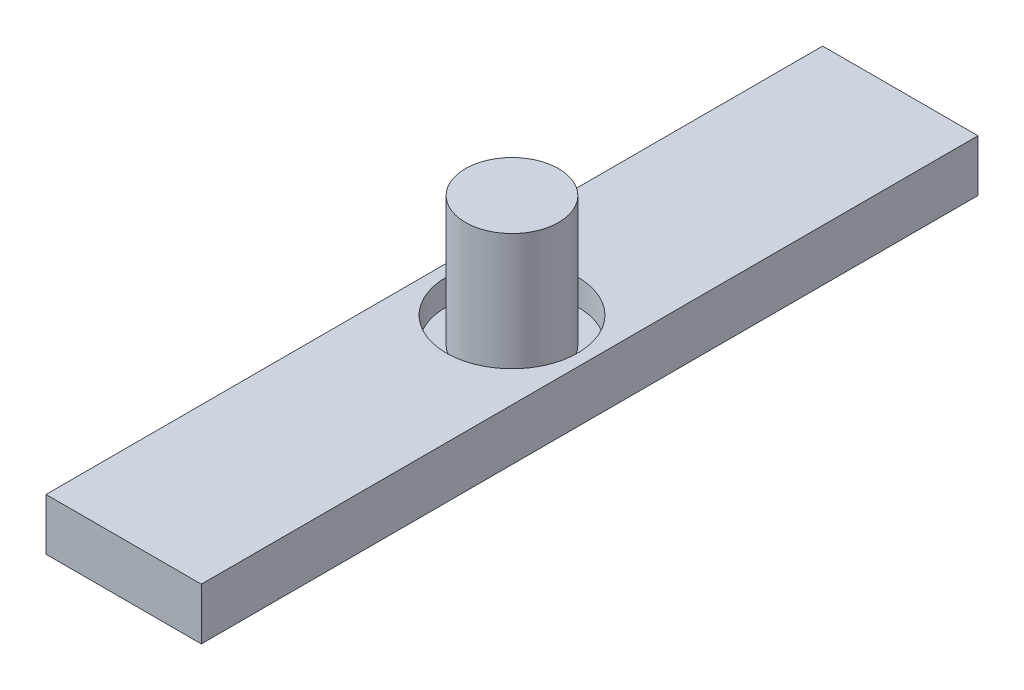
SolidWorks part; units mm, degrees
ref_plane "Front Plane" through (0, 0, 0) normal (0, 0, 1) x (1, 0, 0)
ref_plane "Top Plane" through (0, 0, 0) normal (0, 1, 0) x (1, 0, 0)
ref_plane "Right Plane" through (0, 0, 0) normal (1, 0, 0) x (0, 0, -1)
sketch "Sketch1" plane through (0, 0, 0) normal (0, 1, 0) x (1, 0, 0)
  line L1 (-19.8131, 30.0671) -> (10.1869, 30.0671)
  line L2 (-19.8131, 30.0671) -> (-19.8131, -119.9329)
  line L3 (-19.8131, -119.9329) -> (10.1869, -119.9329)
  line L4 (10.1869, 30.0671) -> (10.1869, -119.9329)
  dimension "D1" = 30
  dimension "D2" = 150
extrude "Boss-Extrude2" add sketch "Sketch1" along normal blind 10
sketch "Sketch3" plane through (0, 10, 0) normal (0, 1, 0) x (1, 0, 0)
  line L0 (-4.8131, 30.0671) -> (-4.8131, -119.9329) construction
  line L1 (10.1869, 30.0671) -> (-19.8131, 30.0671) construction
  line L2 (-19.8131, -119.9329) -> (10.1869, -119.9329) construction
  circle A0 centre (-4.8131, -44.9329) radius 12.7
  circle A1 centre (-4.8131, -44.9329) radius 9
extrude "Cut-Extrude1" cut sketch "Sketch3" against normal blind 5
sketch "Sketch4" plane through (0, 10, 0) normal (0, 1, 0) x (1, 0, 0)
  circle A0 centre (-4.8131, -44.9329) radius 9
  circle A1 centre (-4.8131, -44.9329) radius 9 construction
  dimension "D1" = 0
extrude "Boss-Extrude3" add sketch "Sketch4" along normal blind 20
